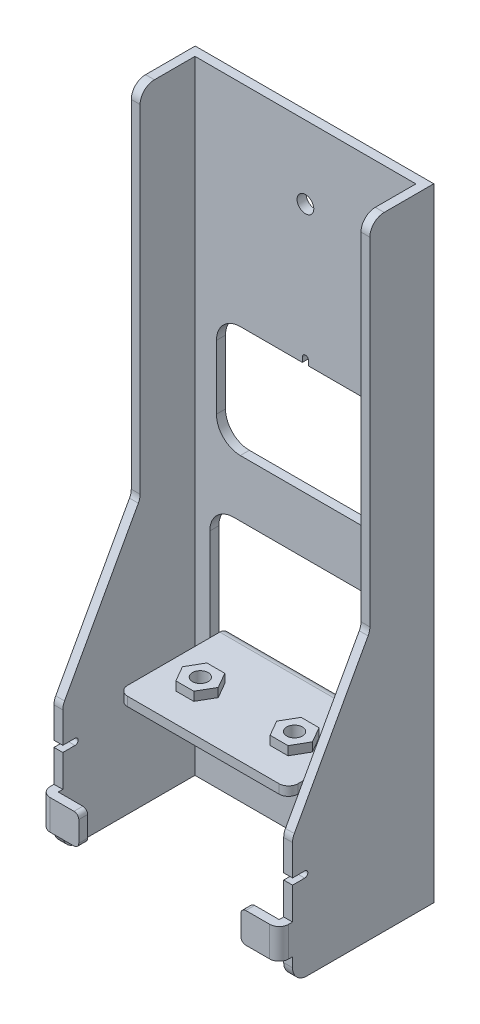
SolidWorks part; units mm, degrees
material "Acier allié inoxydable"
ref_plane "Plan de face" through (0, 0, 0) normal (0, 0, 1) x (1, 0, 0)
ref_plane "Plan de dessus" through (0, 0, 0) normal (0, 1, 0) x (1, 0, 0)
ref_plane "Plan de droite" through (0, 0, 0) normal (1, 0, 0) x (0, 0, -1)
sketch "Esquisse1" plane through (0, 0, 0) normal (0, 0, 1) x (1, 0, 0)
  line L0 (25, 0) -> (2.5, 0)
  line L1 (-25, 0) -> (-25, 130.5)
  line L2 (-25, 130.5) -> (25, 130.5)
  line L3 (25, 130.5) -> (25, 0)
  line L4 (-2.5, 2.8) -> (-2.5, 0)
  line L5 (2.5, 2.8) -> (2.5, 0)
  line L6 (-2.5, 0) -> (-25, 0)
  line L7 (-17.85, 26) -> (-17.85, 28.7)
  line L8 (-15.05, 50.9) -> (15.05, 50.9)
  line L9 (-20.05, 45.9) -> (-20.05, 26)
  line L10 (-17.85, 28.7) -> (17.85, 28.7)
  line L11 (20.05, 45.9) -> (20.05, 26)
  line L12 (-13.65, 86.2) -> (-0.65, 86.2)
  line L13 (-18.65, 81.2) -> (-18.65, 67.8)
  line L14 (-13.65, 62.8) -> (13.65, 62.8)
  line L15 (18.65, 81.2) -> (18.65, 67.8)
  line L16 (17.85, 26) -> (17.85, 28.7)
  line L17 (-0.65, 87.2) -> (-0.65, 86.2)
  line L18 (0.65, 87.2) -> (0.65, 86.2)
  line L19 (0.65, 86.2) -> (13.65, 86.2)
  arc A0 (2.5, 2.8) -> (-2.5, 2.8) centre (0, 2.8) ccw
  circle A1 centre (-18.05, 18.95) radius 1.75
  circle A2 centre (18.05, 18.95) radius 1.75
  arc A3 (-18.65, 67.8) -> (-13.65, 62.8) centre (-13.65, 67.8) ccw
  arc A4 (13.65, 62.8) -> (18.65, 67.8) centre (13.65, 67.8) ccw
  arc A5 (13.65, 86.2) -> (18.65, 81.2) centre (13.65, 81.2) cw
  arc A6 (-13.65, 86.2) -> (-18.65, 81.2) centre (-13.65, 81.2) ccw
  arc A7 (15.05, 50.9) -> (20.05, 45.9) centre (15.05, 45.9) cw
  arc A8 (-15.05, 50.9) -> (-20.05, 45.9) centre (-15.05, 45.9) ccw
  arc A9 (-20.05, 26) -> (-17.85, 26) centre (-18.95, 26) ccw
  arc A10 (17.85, 26) -> (20.05, 26) centre (18.95, 26) ccw
  arc A11 (0.65, 87.2) -> (-0.65, 87.2) centre (0, 87.2) ccw
  circle A12 centre (0, 115.25) radius 1.75
  dimension "D3" = 2.5
  dimension "D5" = 3.5
  dimension "D6" = 3.5
  dimension "D7" = 36.1
  dimension "D8" = 18.05
  dimension "D9" = 18.95
  dimension "D11" = 5
  dimension "D16" = 2.2
  dimension "D17" = 2.2
  dimension "D23" = 0.65
  dimension "D26" = 3.5
  dimension "D1" = 50
  dimension "D2" = 130.5
  dimension "D4" = 2.8
  dimension "D10" = 25
  dimension "D12" = 40.1
  dimension "D13" = 20.05
  dimension "D14" = 28.7
  dimension "D15" = 22.2
  dimension "D18" = 26
  dimension "D19" = 23.4
  dimension "D20" = 37.3
  dimension "D21" = 18.65
  dimension "D22" = 11.9
  dimension "D24" = 0.65
  dimension "D25" = 1
  dimension "D27" = 15.25
extrude "Boss.-Extru.1" add sketch "Esquisse1" along normal blind 1.9
sketch "Esquisse2" plane through (0, 0, 1.9) normal (0, 0, 1) x (1, 0, 0)
  line L0 (17.85, 28.7) -> (17.85, 26) construction
  line L1 (-17.85, 28.7) -> (17.85, 28.7)
  line L2 (-17.85, 28.7) -> (-17.85, 26.8)
  line L3 (-17.85, 26.8) -> (17.85, 26.8)
  line L4 (17.85, 28.7) -> (17.85, 26.8)
  dimension "D1" = 1.9
extrude "Boss.-Extru.2" add sketch "Esquisse2" along normal blind 21.4
fillet "Congé1" radius 2 2 edges at (17.85, 27.75, 23.3) (-17.85, 27.75, 23.3)
fillet "Congé2" radius 0.2 1 edges at (0, 26.8, 1.9)
fillet "Congé3" radius 2 1 edges at (0, 28.7, 0)
sketch "Esquisse3" plane through (0, 28.7, 0) normal (0, 1, 0) x (1, 0, 0)
  line L2 (6.1222, -14.05) -> (7.9986, -17.3)
  line L3 (7.9986, -17.3) -> (11.7514, -17.3)
  line L4 (11.7514, -17.3) -> (13.6278, -14.05)
  line L5 (13.6278, -14.05) -> (11.7514, -10.8)
  line L6 (11.7514, -10.8) -> (7.9986, -10.8)
  line L7 (7.9986, -10.8) -> (6.1222, -14.05)
  line L8 (-6.1222, -14.05) -> (-7.9986, -10.8)
  line L9 (-7.9986, -10.8) -> (-11.7514, -10.8)
  line L10 (-11.7514, -10.8) -> (-13.6278, -14.05)
  line L11 (-13.6278, -14.05) -> (-11.7514, -17.3)
  line L12 (-11.7514, -17.3) -> (-7.9986, -17.3)
  line L13 (-7.9986, -17.3) -> (-6.1222, -14.05)
  circle A0 centre (9.875, -14.05) radius 3.25 construction
  circle A1 centre (-9.875, -14.05) radius 3.25 construction
  dimension "D4" = 6.5
  dimension "D5" = 6.5
extrude "Boss.-Extru.3" add sketch "Esquisse3" along normal blind 1.85
hole_wizard "Trou taraudé M41" positions "Esquisse5" profile "Esquisse4" tap size "M4" standard "ISO" end condition through all
sketch "Esquisse5" plane through (0, 30.55, 0) normal (0, 1, 0) x (-1, 0, 0)
  point P0 (-9.875, 14.05)
  point P1 (9.875, 14.05)
sketch "Esquisse4" plane through (9.875, 30.55, 14.05) normal (1, 0, 0) x (0, 0, 1)
  line L0 (0, 0) -> (0, 30.55)
  line L1 (0, 30.55) -> (1.65, 30.55)
  line L2 (1.65, 30.55) -> (1.65, 0)
  line L5 (1.65, 0) -> (0, 0)
  line L11 (0, -6.35) -> (0, 107.95) construction
  dimension "Diamètre du trou pour taraudage jusqu'au prochain" = 3.3
  dimension "Profondeur du trou pour taraudage jusqu'au prochain" = 30.55
cosmetic thread "Filetage de perçage1" parameters "D2"=4
cosmetic thread "Filetage de perçage2" parameters "D2"=4
sketch "Esquisse6" plane through (-25, 0, 0) normal (-1, 0, 0) x (0, 0, 1)
  line L0 (13.4, 130.5) -> (13.4, 56)
  line L1 (13.4, 56) -> (29.6, 26.5)
  line L2 (29.6, 26.5) -> (29.6, 19.3)
  line L3 (29.6, 19.3) -> (27.05, 19.3)
  line L4 (0, 130.5) -> (0, 0)
  line L5 (0, 0) -> (1.9, 0)
  line L6 (1.9, 0) -> (1.9, 130.5)
  line L7 (1.9, 130.5) -> (0, 130.5)
  line L8 (0, 130.5) -> (0, 0)
  line L9 (29.6, 11.3) -> (32.4, 11.3)
  line L10 (32.4, 11.3) -> (32.4, 5)
  line L11 (13.4, 130.5) -> (0, 130.5)
  line L12 (27.05, 18) -> (29.6, 18)
  line L13 (29.6, 18) -> (29.6, 11.3)
  line L14 (29.6, 0) -> (0, 0)
  line L15 (32.4, 5) -> (29.6, 5)
  line L16 (29.6, 5) -> (29.6, 0)
  arc A0 (27.05, 19.3) -> (27.05, 18) centre (27.05, 18.65) ccw
  dimension "D2" = 13.4
  dimension "D3" = 29.6
  dimension "D4" = 74.5
  dimension "D5" = 26.5
  dimension "D6" = 18
  dimension "D7" = 1.3
  dimension "D8" = 2.55
  dimension "D9" = 6.3
  dimension "D10" = 5
  dimension "D11" = 2.8
  dimension "D1" = 0
extrude "Boss.-Extru.4" add sketch "Esquisse6" against normal blind 1.85
fillet "Congé4" radius 3 4 edges at (-24.075, 26.5, 29.6) (-24.075, 56, 13.4) (-24.075, 130.5, 13.4) (-24.075, 0, 29.6)
sketch "Esquisse7" plane through (0, 0, 32.4) normal (0, 0, 1) x (1, 0, 0)
  line L0 (-23.15, 11.3) -> (-25, 11.3) construction
  line L1 (-25, 5) -> (-17, 5)
  line L2 (-25, 5) -> (-25, 11.3)
  line L3 (-25, 11.3) -> (-17, 11.3)
  line L4 (-17, 5) -> (-17, 11.3)
  dimension "D1" = 8
extrude "Boss.-Extru.5" add sketch "Esquisse7" against normal blind 1.85
fillet "Congé5" radius 1 2 edges at (-17, 11.3, 31.475) (-17, 5, 31.475)
fillet "Congé6" radius 2 1 edges at (-25, 8.15, 32.4)
mirror "Symétrie1" about plane through (0, 0, 0) normal (1, 0, 0) of "Boss.-Extru.4", "Congé4", "Boss.-Extru.5", "Congé5", "Congé6"
